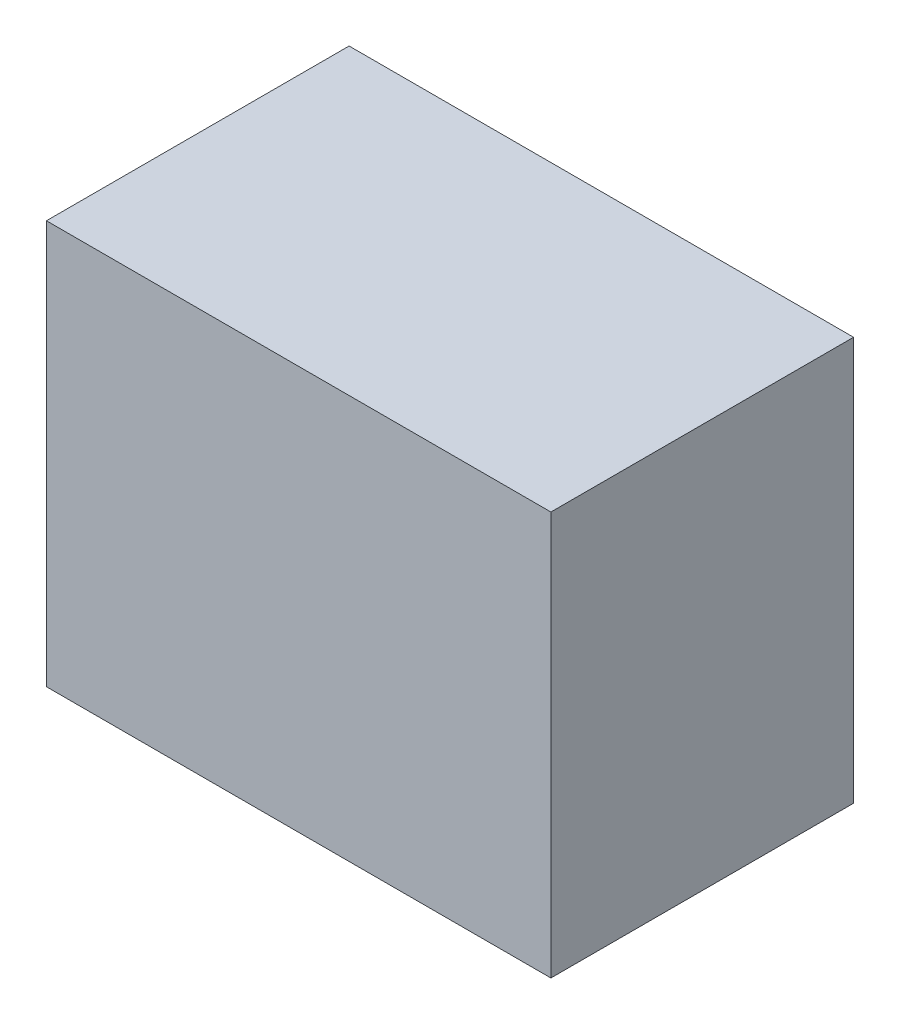
SolidWorks part; units mm, degrees
ref_plane "Front Plane" through (0, 0, 0) normal (0, 0, 1) x (1, 0, 0)
ref_plane "Top Plane" through (0, 0, 0) normal (0, 1, 0) x (1, 0, 0)
ref_plane "Right Plane" through (0, 0, 0) normal (1, 0, 0) x (0, 0, -1)
sketch "Sketch1" plane through (0, 0, 0) normal (0, 1, 0) x (1, 0, 0)
  line L1 (-6.25, 3.75) -> (6.25, 3.75)
  line L2 (-6.25, 3.75) -> (-6.25, -3.75)
  line L3 (-6.25, -3.75) -> (6.25, -3.75)
  line L4 (6.25, 3.75) -> (6.25, -3.75)
  line L5 (-6.25, 3.75) -> (6.25, -3.75) construction
  line L6 (-6.25, -3.75) -> (6.25, 3.75) construction
  point P0 (0, 0)
  dimension "D1" = 12.5
  dimension "D2" = 7.5
extrude "Boss-Extrude1" add sketch "Sketch1" along normal blind 10
